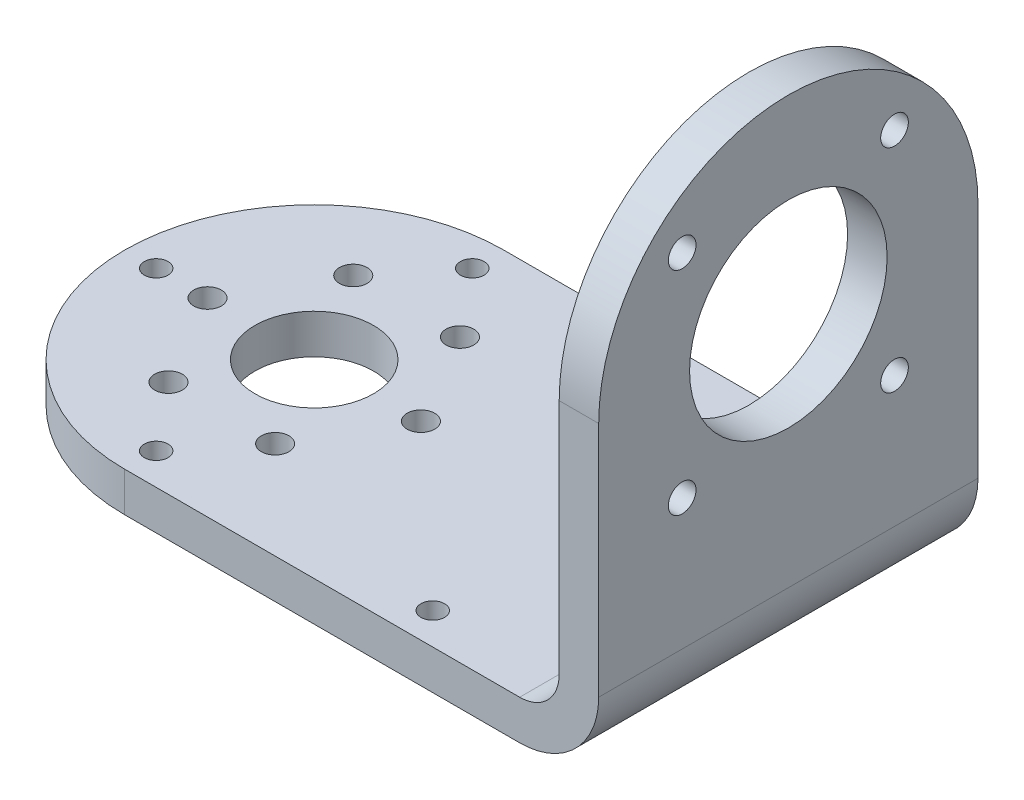
SolidWorks part; units mm, degrees
ref_plane "前视基准面" through (0, 0, 0) normal (0, 0, 1) x (1, 0, 0)
ref_plane "上视基准面" through (0, 0, 0) normal (0, 1, 0) x (1, 0, 0)
ref_plane "右视基准面" through (0, 0, 0) normal (1, 0, 0) x (0, 0, -1)
sketch "草图1" plane through (0, 0, 0) normal (0, 1, 0) x (1, 0, 0)
  line L0 (0, 24) -> (60, 24)
  line L1 (60, 24) -> (60, -24)
  line L2 (60, -24) -> (0, -24)
  line L3 (55, 24) -> (55, -24)
  circle A0 centre (0, 0) radius 24
  dimension "D1" = 48
  dimension "D2" = 60
  dimension "D3" = 5
extrude "凸台-拉伸1" add sketch "草图1" along normal blind 5 contours L2 A0 | A0 L2 L1 L0 | A0 L3 L0 | A0 L2 L3
sketch "草图2" plane through (60, 0, 0) normal (1, 0, 0) x (0, 0, -1)
  line L0 (24, 5) -> (-24, 5) construction
  line L1 (-24, 40) -> (-24, 0)
  line L2 (24, 0) -> (24, 40)
  line L4 (0, 0) -> (0, 79.237) construction
  line L5 (24, 0) -> (-24, 0) construction
  line L6 (-24, 0) -> (24, 0)
  circle A0 centre (0, 40) radius 24
  dimension "D1" = 48
  dimension "D2" = 35
extrude "凸台-拉伸2" add sketch "草图2" against normal blind 5
sketch "草图3" plane through (0, 5, 0) normal (0, 1, 0) x (1, 0, 0)
  circle A0 centre (0, 0) radius 13.5 construction
  circle A1 centre (-13.5, 0) radius 1.75
  circle A2 centre (-6.75, 11.6913) radius 1.75
  circle A3 centre (6.75, 11.6913) radius 1.75
  circle A4 centre (13.5, 0) radius 1.75
  circle A5 centre (6.75, -11.6913) radius 1.75
  circle A6 centre (-6.75, -11.6913) radius 1.75
  point P17 (0, 0)
  dimension "D1" = 27
  dimension "D2" = 3.5
  dimension "D3" = 6
extrude "切除-拉伸1" cut sketch "草图3" against normal blind 21
sketch "草图4" plane through (60, 0, 0) normal (1, 0, 0) x (0, 0, -1)
  line L0 (-24, 40) -> (24, 40) construction
  line L1 (0, 65) -> (0, 0) construction
  line L2 (-13.435, 53.435) -> (0, 40) construction
  circle A0 centre (0, 40) radius 19 construction
  circle A1 centre (0, 40) radius 24 construction
  circle A2 centre (-13.435, 53.435) radius 1.75
  circle A3 centre (13.435, 53.435) radius 1.75
  circle A4 centre (13.435, 26.565) radius 1.75
  circle A5 centre (-13.435, 26.565) radius 1.75
  point P24 (0, 40)
  dimension "D1" = 38
  dimension "D3" = 3.5
  dimension "D2" = 45
  dimension "D4" = 4
extrude "切除-拉伸2" cut sketch "草图4" against normal blind 21
fillet "圆角1" radius 5 1 edges at (55, 5, 0)
fillet "圆角2" radius 10 1 edges at (60, 0, 0)
sketch "草图6" plane through (0, 5, 0) normal (0, 1, 0) x (1, 0, 0)
  line L0 (0, 20) -> (37.3479, 20) construction
  line L1 (0, 0) -> (68.729, 0) construction
  circle A0 centre (0, 0) radius 20 construction
  circle A1 centre (0, 20) radius 1.5
  circle A2 centre (35, 20) radius 1.5
  circle A3 centre (35, -20) radius 1.5
  circle A4 centre (0, -20) radius 1.5
  circle A5 centre (-20, 0) radius 1.5
  dimension "D1" = 40
  dimension "D2" = 3
  dimension "D3" = 3
  dimension "D5" = 3
  dimension "D4" = 35
extrude "切除-拉伸4" cut sketch "草图6" against normal blind 10
sketch "草图7" plane through (0, 5, 0) normal (0, 1, 0) x (1, 0, 0)
  circle A0 centre (0, 0) radius 7.5
  dimension "D1" = 15
extrude "切除-拉伸5" cut sketch "草图7" against normal blind 10
sketch "草图8" plane through (60, 0, 0) normal (1, 0, 0) x (0, 0, -1)
  circle A0 centre (0, 40) radius 12.5
  dimension "D1" = 25
extrude "切除-拉伸6" cut sketch "草图8" against normal blind 10
sketch "草图9" plane through (0, 0, 0) normal (0, -1, 0) x (1, 0, 0)
  circle A0 centre (-6.75, 11.6913) radius 3
  circle A1 centre (6.75, 11.6913) radius 3
  circle A2 centre (6.75, -11.6913) radius 3
  circle A3 centre (-6.75, -11.6913) radius 3
  circle A4 centre (-13.5, 0) radius 3
  circle A5 centre (13.5, 0) radius 3
  dimension "D1" = 6
  dimension "D2" = 6
  dimension "D3" = 6
  dimension "D4" = 6
  dimension "D5" = 6
  dimension "D6" = 6
extrude "切除-拉伸7" [suppressed] cut sketch "草图9" against normal blind 3
sketch "草图12" plane through (55, 0, 0) normal (-1, 0, 0) x (0, 0, 1)
  circle A0 centre (-13.435, 53.435) radius 3
  circle A1 centre (13.435, 53.435) radius 3
  circle A2 centre (13.435, 26.565) radius 3
  circle A3 centre (-13.435, 26.565) radius 3
  dimension "D1" = 6
  dimension "D2" = 6
  dimension "D3" = 6
  dimension "D4" = 6
extrude "切除-拉伸8" [suppressed] cut sketch "草图12" against normal blind 3
